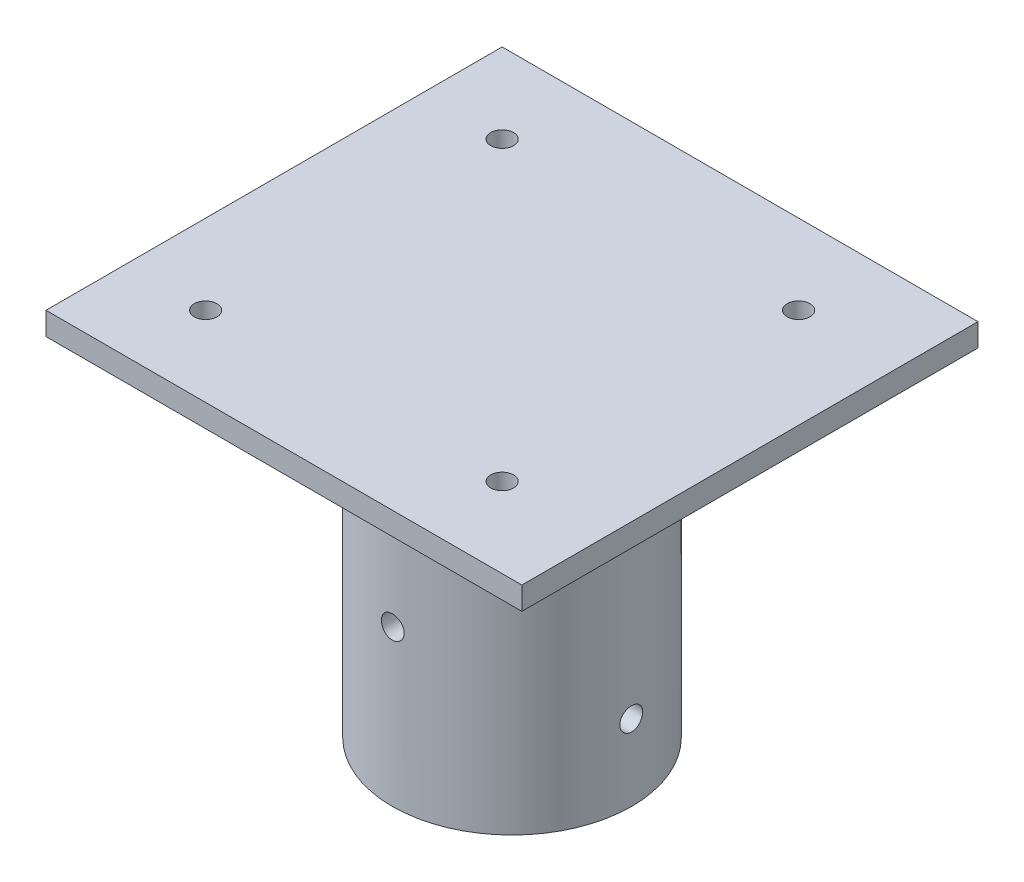
SolidWorks part; units mm, degrees
ref_plane "Front Plane" through (0, 0, 0) normal (0, 0, 1) x (1, 0, 0)
ref_plane "Top Plane" through (0, 0, 0) normal (0, 1, 0) x (1, 0, 0)
ref_plane "Right Plane" through (0, 0, 0) normal (1, 0, 0) x (0, 0, -1)
sketch "Sketch1" plane through (0, 0, 0) normal (0, 1, 0) x (1, 0, 0)
  line L1 (26.4989, -25.4) -> (-26.4989, -25.4)
  line L2 (26.4989, -25.4) -> (26.4989, 25.4)
  line L3 (26.4989, 25.4) -> (-26.4989, 25.4)
  line L4 (-26.4989, -25.4) -> (-26.4989, 25.4)
  line L5 (26.4989, -25.4) -> (-26.4989, 25.4) construction
  line L6 (26.4989, 25.4) -> (-26.4989, -25.4) construction
  point P0 (0, 0)
  dimension "D1" = 50.8
extrude "Boss-Extrude1" add sketch "Sketch1" along normal blind 2.54 contours L1 L4 L3 L2
sketch "Sketch2" plane through (0, 0, 0) normal (0, -1, 0) x (1, 0, 0)
  line L0 (-17.6089, 25.4) -> (-17.6089, 16.51) construction
  line L1 (26.4989, 25.4) -> (-26.4989, 25.4) construction
  line L2 (-17.6089, 16.51) -> (-26.4989, 16.51) construction
  line L3 (-26.4989, 25.4) -> (-26.4989, -25.4) construction
  circle A0 centre (-17.6089, 16.51) radius 1.27
  dimension "D2" = 2.54
  dimension "D1" = 8.89
extrude "Cut-Extrude1" cut sketch "Sketch2" against normal through all
pattern_linear "LPattern1" count 2 spacing 33.02 along (1, 0, 0) count 2 spacing 33.02 along (0, 0, -1) of "Cut-Extrude1"
sketch "Sketch3" plane through (0, 0, 0) normal (0, -1, 0) x (1, 0, 0)
  circle A0 centre (0, 0) radius 9.525
  circle A1 centre (0, 0) radius 13.335
  dimension "D1" = 19.05
  dimension "D2" = 3.81
extrude "Boss-Extrude2" add sketch "Sketch3" along normal blind 38.1
ref_plane "Plane2" through (0, 0, 13.335) normal (0, 0, 1) x (1, 0, 0)
sketch "Sketch4" plane through (0, 0, 13.335) normal (0, 0, 1) x (1, 0, 0)
  circle A0 centre (0, -20.7838) radius 1.27
  dimension "D1" = 2.54
extrude "Cut-Extrude2" cut sketch "Sketch4" against normal blind 7.62
ref_plane "Plane3" through (13.335, 0, 0) normal (1, 0, 0) x (0, 0, -1)
sketch "Sketch5" plane through (13.335, 0, 0) normal (1, 0, 0) x (0, 0, -1)
  circle A0 centre (0, -29.6392) radius 1.27
  dimension "D1" = 2.54
extrude "Cut-Extrude3" cut sketch "Sketch5" against normal blind 7.62
